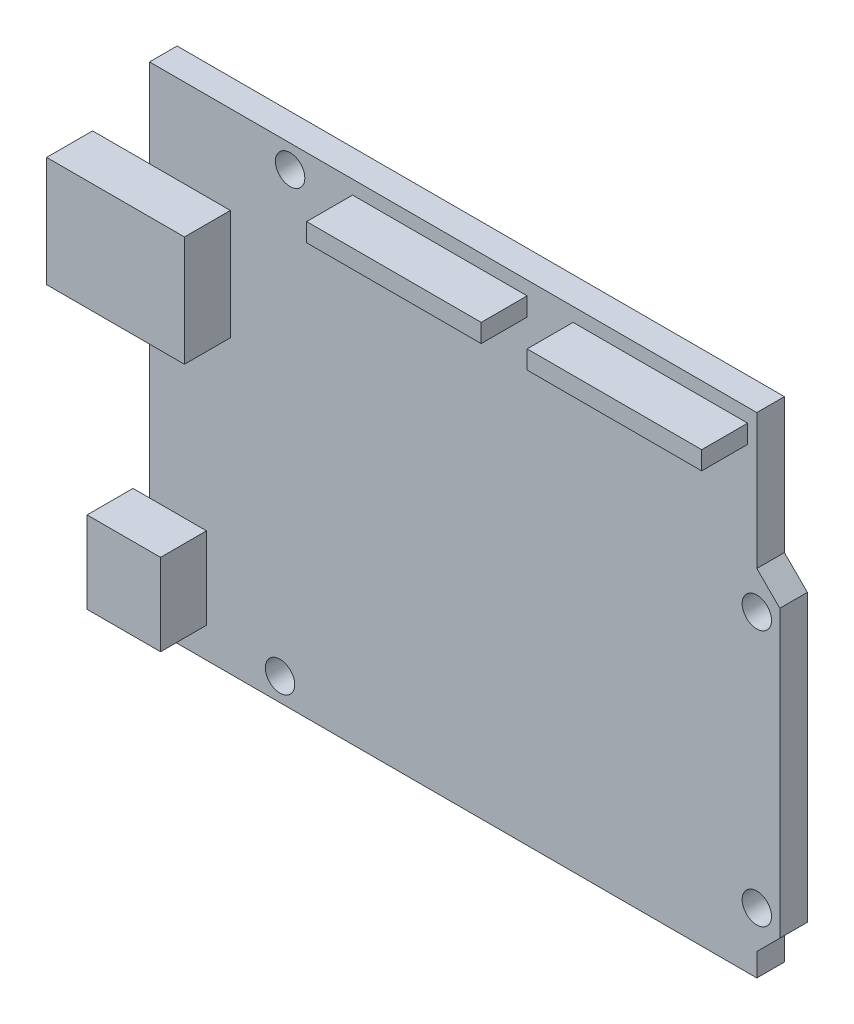
SolidWorks part; units mm, degrees
ref_plane "Alzado" through (0, 0, 0) normal (0, 0, 1) x (1, 0, 0)
ref_plane "Planta" through (0, 0, 0) normal (0, 1, 0) x (1, 0, 0)
ref_plane "Vista lateral" through (0, 0, 0) normal (1, 0, 0) x (0, 0, -1)
sketch "Croquis1" plane through (0, 0, 0) normal (0, 0, 1) x (1, 0, 0)
  line L0 (-33.05, 26.65) -> (-33.05, -26.65)
  line L1 (-33.05, -26.65) -> (33.05, -26.65)
  line L2 (33.05, -26.65) -> (33.05, -24.15)
  line L3 (33.05, -24.15) -> (35.55, -21.65)
  line L4 (35.55, -21.65) -> (35.55, 9.45)
  line L5 (35.55, 9.45) -> (33.05, 11.95)
  line L6 (33.05, 11.95) -> (33.05, 26.65)
  line L7 (33.05, 26.65) -> (-33.05, 26.65)
  circle A0 centre (33.05, -20.05) radius 1.6
  circle A1 centre (33.05, 7.85) radius 1.6
  circle A2 centre (-18.85, -24.15) radius 1.6
  circle A3 centre (-17.75, 24.15) radius 1.6
  point P9 (-33.05, 0)
  point P10 (0, -26.65)
  point P19 (0, 0)
  point P20 (0, 0)
  point P21 (0, 0)
  point P22 (0, 0)
  dimension "D6" = 3.2
  dimension "D1" = 53.3
  dimension "D2" = 2.5
  dimension "D3" = 2.5
  dimension "D4" = 2.5
  dimension "D5" = 68.6
  dimension "D7" = 27.9
  dimension "D8" = 51.9
  dimension "D9" = 50.8
  dimension "D10" = 2.5
  dimension "D11" = 1.6
  dimension "D12" = 31.1
  dimension "D13" = 2.5
extrude "Saliente-Extruir1" add sketch "Croquis1" along normal blind 3
sketch "Croquis2" plane through (0, 0, 3) normal (0, 0, 1) x (1, 0, 0)
  line L0 (-33.05, -23.35) -> (-33.05, -26.65)
  line L1 (-39.25, 17.05) -> (-24.25, 17.05)
  line L2 (-39.25, 17.05) -> (-39.25, 5.05)
  line L3 (-39.25, 5.05) -> (-24.25, 5.05)
  line L4 (-24.25, 17.05) -> (-24.25, 5.05)
  line L5 (-34.85, -14.45) -> (-26.85, -14.45)
  line L6 (-34.85, -14.45) -> (-34.85, -23.35)
  line L7 (-34.85, -23.35) -> (-26.85, -23.35)
  line L8 (33.05, 26.65) -> (-33.05, 26.65)
  line L9 (-33.05, 26.65) -> (-33.05, -26.65)
  line L10 (-33.05, -26.65) -> (33.05, -26.65)
  line L11 (33.05, -26.65) -> (33.05, -24.15)
  line L12 (33.05, -24.15) -> (35.55, -21.65)
  line L13 (35.55, -21.65) -> (35.55, 9.45)
  line L14 (35.55, 9.45) -> (33.05, 11.95)
  line L15 (33.05, 11.95) -> (33.05, 26.65)
  line L16 (33.05, 26.65) -> (-33.05, 26.65)
  line L17 (-33.05, 26.65) -> (-33.05, 17.05)
  line L18 (-33.05, -26.65) -> (33.05, -26.65)
  line L19 (33.05, -26.65) -> (33.05, -24.15)
  line L20 (33.05, -24.15) -> (35.55, -21.65)
  line L21 (35.55, -21.65) -> (35.55, 9.45)
  line L22 (35.55, 9.45) -> (33.05, 11.95)
  line L23 (33.05, 11.95) -> (33.05, 26.65)
  line L24 (-26.85, -14.45) -> (-26.85, -23.35)
  line L25 (-10.95, 25.15) -> (8.05, 25.15)
  line L26 (-10.95, 25.15) -> (-10.95, 23.15)
  line L27 (-10.95, 23.15) -> (8.05, 23.15)
  line L28 (8.05, 25.15) -> (8.05, 23.15)
  line L29 (13.05, 25.15) -> (32.05, 25.15)
  line L30 (13.05, 25.15) -> (13.05, 23.15)
  line L31 (13.05, 23.15) -> (32.05, 23.15)
  line L32 (32.05, 25.15) -> (32.05, 23.15)
  line L33 (-33.05, 5.05) -> (-33.05, -14.45)
  circle A0 centre (-17.75, 24.15) radius 1.6 construction
  circle A1 centre (-17.75, 24.15) radius 1.6
  point P31 (0, 0)
  point P32 (-10.95, 24.15)
  point P33 (8.05, 24.15)
  point P34 (13.05, 24.15)
  line M28 (-33.05, 26.65) -> (-33.05, -26.65)
  dimension "D8" = 15
  dimension "D2" = 12
  dimension "D3" = 6.2
  dimension "D4" = 8.9
  dimension "D5" = 3.3
  dimension "D6" = 1.8
  dimension "D7" = 9.6
  dimension "D9" = 8
  dimension "D10" = 19
  dimension "D11" = 19
  dimension "D12" = 2
  dimension "D13" = 1
  dimension "D14" = 5
  dimension "D1" = 0
extrude "Saliente-Extruir2" add sketch "Croquis2" along normal blind 5 contours L4 L1 L3 M28 | L24 L5 L7 M28 | L2 L3 L1 M28 | L6 L7 L5 M28 | L32 L29 L30 L31 | L28 L25 L26 L27
